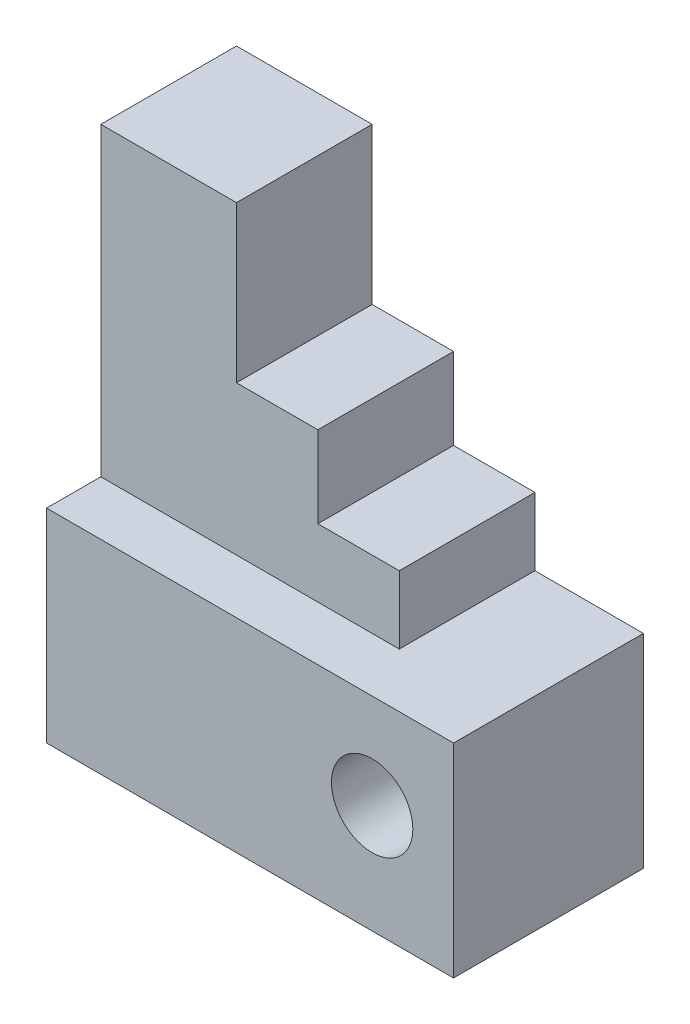
SolidWorks part; units mm, degrees
material "Plain Carbon Steel"
ref_plane "Front Plane" through (0, 0, 0) normal (0, 0, 1) x (1, 0, 0)
ref_plane "Top Plane" through (0, 0, 0) normal (0, 1, 0) x (1, 0, 0)
ref_plane "Right Plane" through (0, 0, 0) normal (1, 0, 0) x (0, 0, -1)
sketch "Sketch1" plane through (0, 0, 0) normal (0, 0, 1) x (1, 0, 0)
  line L1 (0, 0) -> (60, 0)
  line L2 (0, 0) -> (0, 30)
  line L3 (0, 30) -> (60, 30)
  line L4 (60, 0) -> (60, 30)
  circle A0 centre (48, 16) radius 6
  dimension "D4" = 12
  dimension "D1" = 60
  dimension "D2" = 48
  dimension "D3" = 16
  dimension "D5" = 30
extrude "Boss-Extrude3" add sketch "Sketch1" along normal blind 28
sketch "Sketch4" plane through (0, 0, 0) normal (0, 0, 1) x (1, 0, 0)
  line L0 (44, 30) -> (44, 40)
  line L1 (60, 30) -> (0, 30) construction
  line L2 (44, 40) -> (32, 40)
  line L3 (32, 40) -> (32, 52)
  line L4 (32, 52) -> (20, 52)
  line L5 (20, 52) -> (20, 75)
  line L6 (20, 75) -> (0, 75)
  line L7 (0, 75) -> (0, 30)
  line L8 (0, 0) -> (60, 0) construction
  line L13 (0, 30) -> (0, 0)
  line L14 (0, 0) -> (60, 0)
  line L15 (60, 0) -> (60, 30)
  line L16 (60, 30) -> (0, 30)
  line L20 (44, 30) -> (0, 30)
  dimension "D1" = 40
  dimension "D2" = 52
  dimension "D3" = 75
  dimension "D4" = 20
  dimension "D5" = 32
  dimension "D6" = 44
  dimension "D7" = 0
extrude "Boss-Extrude4" add sketch "Sketch4" along normal blind 20
